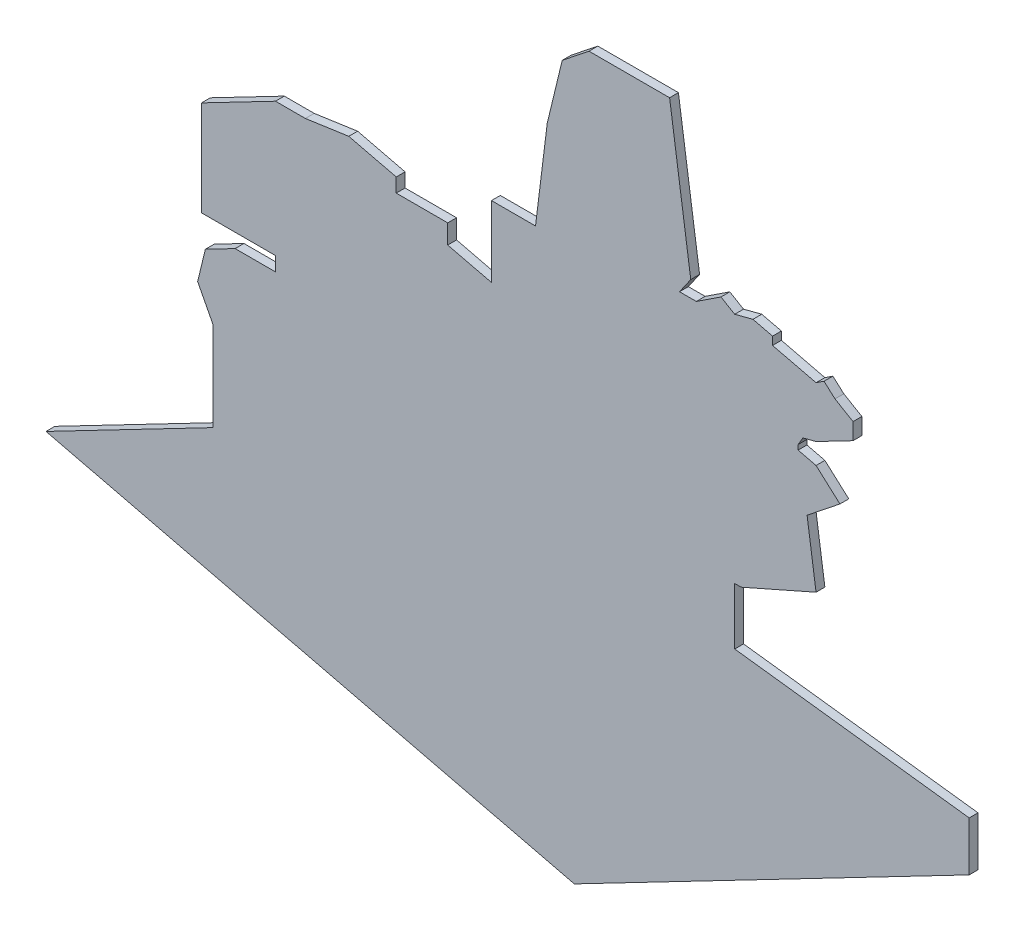
SolidWorks part; units mm, degrees
ref_plane "Ebene vorne" through (0, 0, 0) normal (0, 0, 1) x (1, 0, 0)
ref_plane "Ebene oben" through (0, 0, 0) normal (0, 1, 0) x (1, 0, 0)
ref_plane "Ebene rechts" through (0, 0, 0) normal (1, 0, 0) x (0, 0, -1)
sketch "Skizze1" plane through (0, 0, 0) normal (0, 0, 1) x (1, 0, 0)
  line L8 (40.1804, 84.8648) -> (200.9019, 84.8648) construction
  line L9 (126.216, 93.7231) -> (130.0259, 93.7231)
  line L10 (130.0259, 93.7231) -> (135.5956, 97.3895)
  line L11 (135.5956, 97.3895) -> (138.7183, 95.5563)
  line L12 (138.7183, 95.5563) -> (142.8447, 96.63)
  line L13 (142.8447, 96.63) -> (147.2868, 95.5563)
  line L14 (147.2868, 95.5563) -> (147.2868, 93.7231)
  line L15 (147.2868, 93.7231) -> (157.1382, 91.3421)
  line L16 (157.1382, 91.3421) -> (158.9467, 92.5326)
  line L17 (158.9467, 92.5326) -> (161.4251, 90.3119)
  line L18 (161.4251, 90.3119) -> (165.5211, 87.9073)
  line L19 (165.5211, 87.9073) -> (165.5211, 84.1587)
  line L20 (165.5211, 84.1587) -> (157.1382, 79.8017)
  line L21 (157.1382, 79.8017) -> (154.1618, 79.0273)
  line L22 (154.1618, 79.0273) -> (153.075, 77.176)
  line L23 (153.075, 77.176) -> (153.075, 76.0883)
  line L24 (153.075, 76.0883) -> (157.1382, 75.1063)
  line L25 (157.1382, 75.1063) -> (158.9467, 73.4857)
  line L26 (158.9467, 73.4857) -> (162.55, 70.257)
  line L27 (162.55, 70.257) -> (155.1066, 64.3351)
  line L28 (155.1066, 64.3351) -> (157.1382, 50.2404)
  line L29 (157.1382, 50.2404) -> (140.181, 42.7526)
  line L30 (140.181, 42.7526) -> (138.7183, 42.7526)
  line L31 (138.7183, 42.7526) -> (138.7183, 29.8951)
  line L32 (138.7183, 29.8951) -> (191.819, 23.319)
  line L33 (191.819, 23.319) -> (191.819, 12.136)
  line L34 (191.819, 12.136) -> (102.3921, -34.3439)
  line L35 (102.3921, -34.3439) -> (-17.2731, -5.4217)
  line L36 (-17.2731, -5.4217) -> (20.5629, 14.2437)
  line L37 (20.5629, 14.2437) -> (20.5629, 34.4494)
  line L38 (20.5629, 34.4494) -> (17.0793, 41.1519)
  line L39 (17.0793, 41.1519) -> (18.8211, 48.3586)
  line L40 (18.8211, 48.3586) -> (25.5565, 51.8593)
  line L41 (25.5565, 51.8593) -> (34.7024, 51.8593)
  line L42 (34.7024, 51.8593) -> (34.7024, 55.0625)
  line L43 (34.7024, 55.0625) -> (17.9502, 55.0625)
  line L44 (17.9502, 55.0625) -> (17.9502, 76.6322)
  line L45 (17.9502, 76.6322) -> (34.7024, 85.3392)
  line L46 (34.7024, 85.3392) -> (41.4697, 85.3392)
  line L47 (41.4697, 85.3392) -> (51.3034, 86.7566)
  line L48 (51.3034, 86.7566) -> (62.0521, 84.1587)
  line L49 (62.0521, 84.1587) -> (62.0521, 80.9857)
  line L50 (62.0521, 80.9857) -> (73.7183, 80.9857)
  line L51 (73.7183, 80.9857) -> (73.7183, 76.6322)
  line L52 (73.7183, 76.6322) -> (83.623, 74.2383)
  line L53 (83.623, 74.2383) -> (83.623, 90.3119)
  line L54 (83.623, 90.3119) -> (93.5949, 90.3119)
  line L55 (93.5949, 90.3119) -> (96.2534, 111.7786)
  line L56 (96.2534, 111.7786) -> (99.6498, 125.8314)
  line L57 (99.6498, 125.8314) -> (105.714, 130.6561)
  line L58 (105.714, 130.6561) -> (123.9664, 130.6561)
  line L59 (123.9664, 130.6561) -> (126.216, 115.049)
  line L60 (126.216, 115.049) -> (128.7614, 97.3895)
  line L61 (128.7614, 97.3895) -> (126.216, 93.7231)
  point P55 (102.3921, -34.3439)
  dimension "D1" = 165
extrude "Aufsatz-Linear austragen1" add sketch "Skizze1" along normal blind 2
